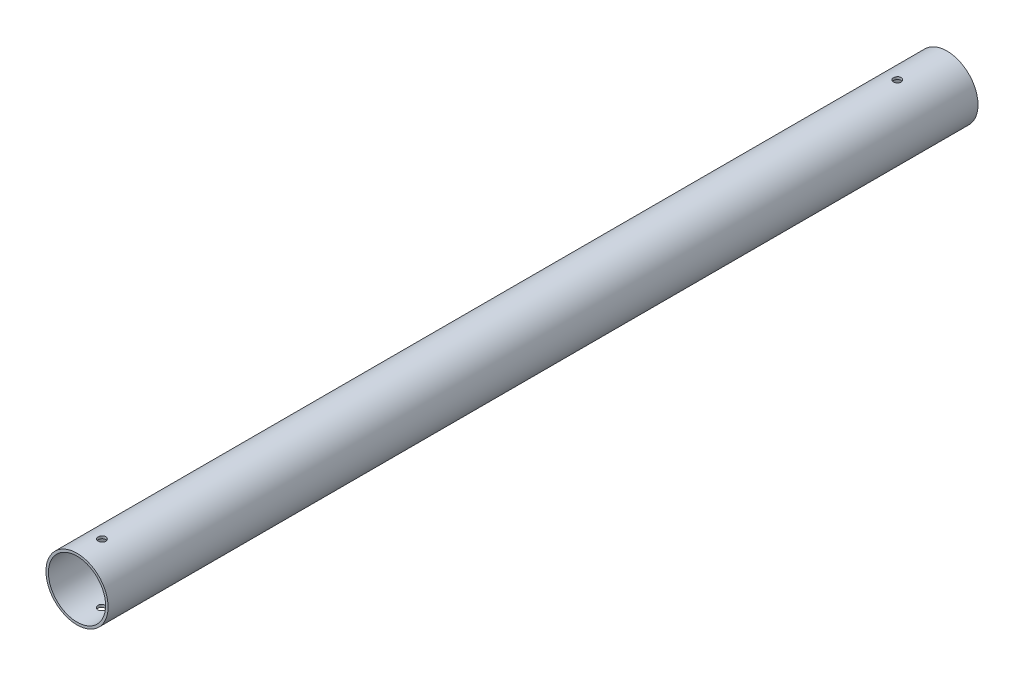
SolidWorks part; units mm, degrees
material "CF-ntbk"
ref_plane "Front Plane" through (0, 0, 0) normal (0, 0, 1) x (1, 0, 0)
ref_plane "Top Plane" through (0, 0, 0) normal (0, 1, 0) x (1, 0, 0)
ref_plane "Right Plane" through (0, 0, 0) normal (1, 0, 0) x (0, 0, -1)
sketch "Sketch1" plane through (0, 0, 0) normal (0, 0, 1) x (1, 0, 0)
  circle A0 centre (0, 0) radius 11.5
  circle A1 centre (0, 0) radius 12.5
  dimension "D1" = 25
  dimension "D2" = 23
extrude "Boss-Extrude1" add sketch "Sketch1" along normal mid plane 350
sketch "Sketch2" plane through (0, 0, 0) normal (0, 1, 0) x (1, 0, 0)
  line L0 (12.5, 175) -> (-12.5, 175) construction
  line L2 (12.5, -175) -> (12.5, 175) construction
  circle A0 centre (0, 155) radius 1.55
  dimension "D2" = 3.1
  dimension "D1" = 20
  dimension "D3" = 12.5
extrude "Cut-Extrude1" cut sketch "Sketch2" against normal mid plane 25
sketch "Sketch3" plane through (0, 0, 0) normal (0, 1, 0) x (1, 0, 0)
  line L0 (-12.5, -175) -> (12.5, -175) construction
  line L1 (12.5, -175) -> (12.5, 175) construction
  circle A0 centre (0, -165) radius 1.55
  dimension "D3" = 3.1
  dimension "D1" = 10
  dimension "D2" = 12.5
extrude "Cut-Extrude2" cut sketch "Sketch3" against normal mid plane 25
equation "\"TubeDiam\"=25"
equation "\"D1@Sketch1\"=\"TubeDiam\""
equation "\"D2@Sketch1\"=\"TubeDiam\"-2"
equation "\"TubeLength\"=350"
equation "\"D1@Boss-Extrude1\"=\"TubeLength\""
equation "\"MountHoleSize\"=3.1"
equation "\"D2@Sketch2\"=\"MountHoleSize\""
equation "\"MountHoleDist\"=20"
equation "\"D1@Sketch2\"=\"MountHoleDist\""
equation "\"D1@Cut-Extrude1\"=\"TubeDiam\""
equation "\"D2@Sketch3\"=\"TubeDiam\"/2"
equation "\"D3@Sketch3\"=\"MountHoleSize\""
equation "\"D1@Cut-Extrude2\"=\"TubeDiam\""
